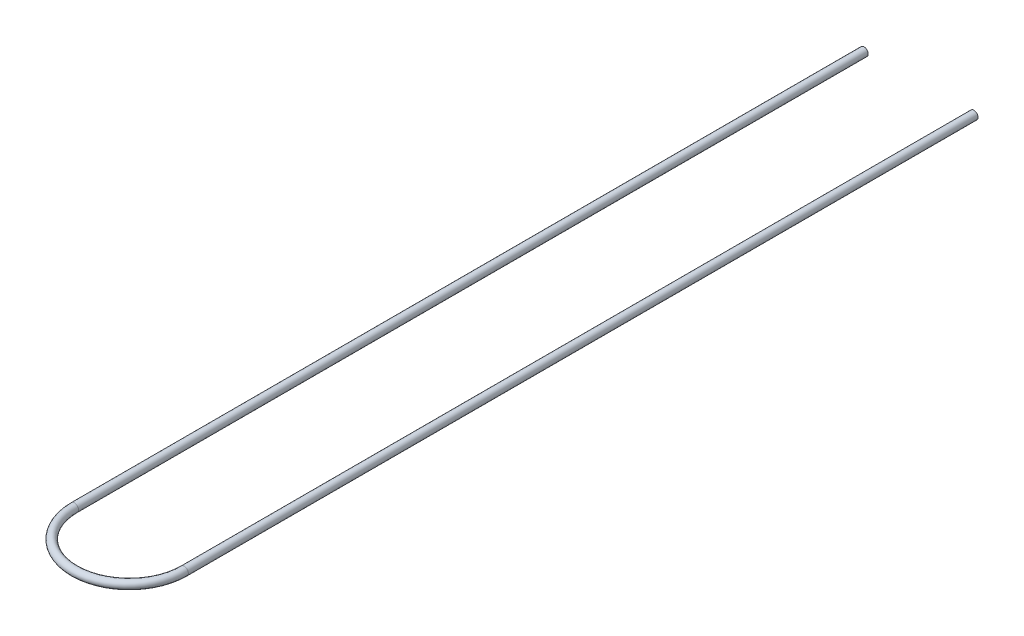
SolidWorks part; units mm, degrees
ref_plane "Front Plane" through (0, 0, 0) normal (0, 0, 1) x (1, 0, 0)
ref_plane "Top Plane" through (0, 0, 0) normal (0, 1, 0) x (1, 0, 0)
ref_plane "Right Plane" through (0, 0, 0) normal (1, 0, 0) x (0, 0, -1)
sketch "Sketch1" plane through (0, 0, 0) normal (0, 1, 0) x (1, 0, 0)
  line L0 (257.54, -300) -> (257.54, -2440)
  line L2 (-40, -300) -> (-40, -2440)
  arc A0 (-40, -2440) -> (257.54, -2440) centre (108.77, -2440) ccw
  dimension "D1" = 2140
  dimension "D2" = 297.54
ref_plane "Plane1" through (257.54, 0, 300) normal (0, 0, -1) x (-1, 0, 0)
sketch "Sketch2" plane through (257.54, 0, 300) normal (0, 0, -1) x (-1, 0, 0)
  circle A0 centre (0, 0) radius 9.95
  circle A1 centre (0, 0) radius 11.1
  dimension "D1" = 22.2
  dimension "D2" = 19.9
sweep "Sweep1" add profiles "Sketch2" path "Sketch1"
